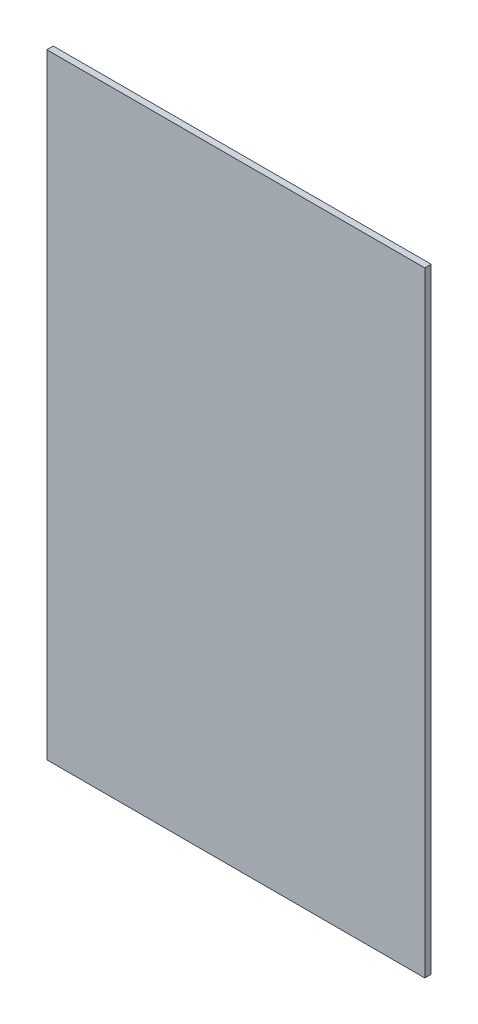
SolidWorks part; units mm, degrees
ref_plane "Front Plane" through (0, 0, 0) normal (0, 0, 1) x (1, 0, 0)
ref_plane "Top Plane" through (0, 0, 0) normal (0, 1, 0) x (1, 0, 0)
ref_plane "Right Plane" through (0, 0, 0) normal (1, 0, 0) x (0, 0, -1)
sketch "Sketch1" plane through (0, 0, 0) normal (0, 0, 1) x (1, 0, 0)
  line L1 (-93.6625, -152.4) -> (93.6625, -152.4)
  line L2 (-93.6625, -152.4) -> (-93.6625, 152.4)
  line L3 (-93.6625, 152.4) -> (93.6625, 152.4)
  line L4 (93.6625, -152.4) -> (93.6625, 152.4)
  line L5 (-93.6625, -152.4) -> (93.6625, 152.4) construction
  line L6 (-93.6625, 152.4) -> (93.6625, -152.4) construction
  point P0 (0, 0)
  dimension "D1" = 187.325
  dimension "D2" = 304.8
extrude "Boss-Extrude1" add sketch "Sketch1" along normal blind 3.175
